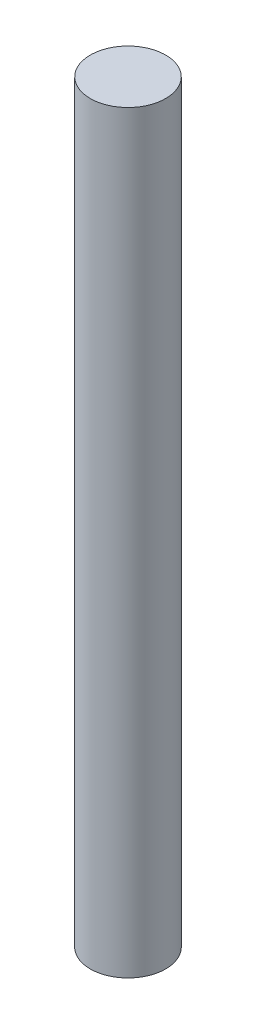
SolidWorks part; units mm, degrees
ref_plane "Front Plane" through (0, 0, 0) normal (0, 0, 1) x (1, 0, 0)
ref_plane "Top Plane" through (0, 0, 0) normal (0, 1, 0) x (1, 0, 0)
ref_plane "Right Plane" through (0, 0, 0) normal (1, 0, 0) x (0, 0, -1)
sketch "Sketch1" plane through (0, 0, 0) normal (0, 1, 0) x (1, 0, 0)
  circle A0 centre (0, 0) radius 10
  dimension "D1" = 20
extrude "Boss-Extrude1" add sketch "Sketch1" along normal blind 200
